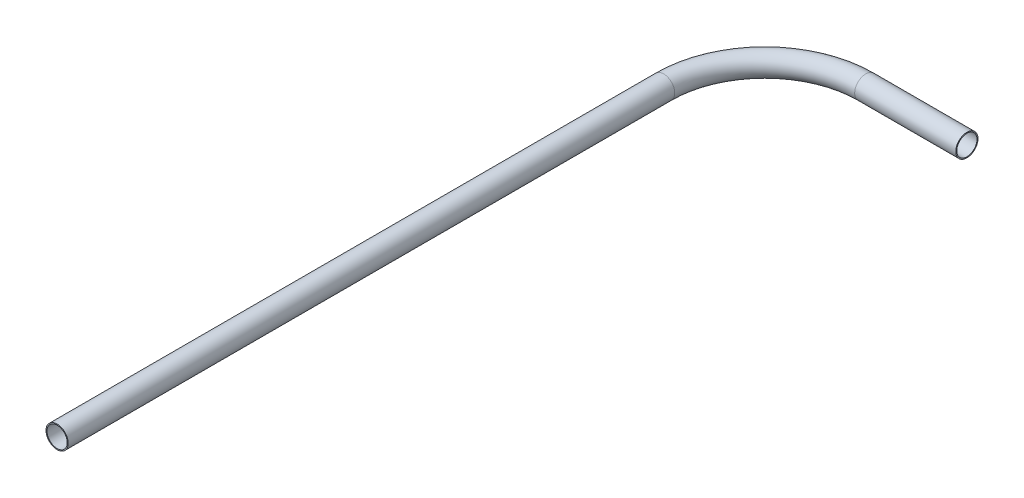
SolidWorks part; units mm, degrees
material "Alumina"
ref_plane "Front Plane" through (0, 0, 0) normal (0, 0, 1) x (1, 0, 0)
ref_plane "Top Plane" through (0, 0, 0) normal (0, 1, 0) x (1, 0, 0)
ref_plane "Right Plane" through (0, 0, 0) normal (1, 0, 0) x (0, 0, -1)
sketch "Sketch2" plane through (0, 0, 0) normal (0, 1, 0) x (1, 0, 0)
  line L0 (0, 0) -> (0, 152.4)
  line L1 (25.4, 177.8) -> (50.8, 177.8)
  arc A0 (0, 152.4) -> (25.4, 177.8) centre (25.4, 152.4) cw
  dimension "D3" = 25.4
  dimension "D1" = 152.4
  dimension "D2" = 25.4
sketch "Sketch4" plane through (0, 0, 0) normal (0, 0, 1) x (1, 0, 0)
  circle A0 centre (0, 0) radius 2.54
  dimension "D1" = 5.08
sweep "Sweep-Thin1" add profiles "Sketch4" path "Sketch2" parameters "D1"=0.254
